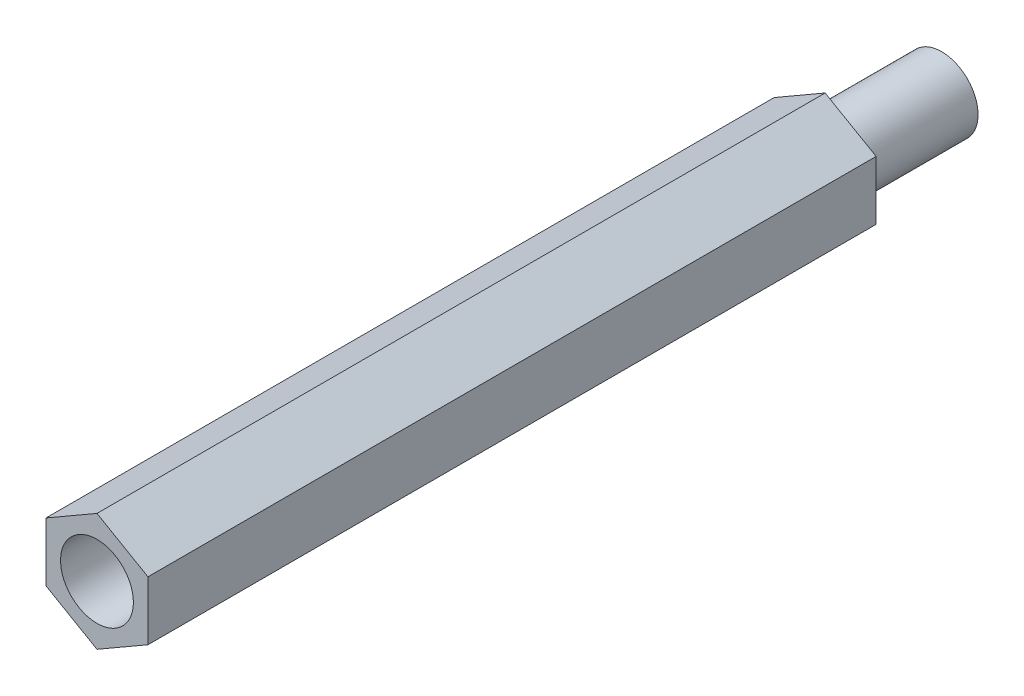
SolidWorks part; units mm, degrees
ref_plane "前视基准面" through (0, 0, 0) normal (0, 0, 1) x (1, 0, 0)
ref_plane "上视基准面" through (0, 0, 0) normal (0, 1, 0) x (1, 0, 0)
ref_plane "右视基准面" through (0, 0, 0) normal (1, 0, 0) x (0, 0, -1)
sketch "草图1" plane through (0, 0, 0) normal (0, 0, 1) x (1, 0, 0)
  line L1 (3.5, -2.0207) -> (3.5, 2.0207)
  line L2 (3.5, 2.0207) -> (0, 4.0415)
  line L3 (0, 4.0415) -> (-3.5, 2.0207)
  line L4 (-3.5, 2.0207) -> (-3.5, -2.0207)
  line L5 (-3.5, -2.0207) -> (0, -4.0415)
  line L6 (0, -4.0415) -> (3.5, -2.0207)
  circle A0 centre (0, 0) radius 3.5 construction
  dimension "D1" = 7
extrude "凸台-拉伸1" add sketch "草图1" along normal blind 60
sketch "草图2" plane through (0, 0, 0) normal (0, 0, -1) x (-1, 0, 0)
  circle A0 centre (0, 0) radius 2.5
extrude "凸台-拉伸2" add sketch "草图2" along normal blind 8
sketch "草图3" plane through (0, 0, 60) normal (0, 0, 1) x (1, 0, 0)
  circle A0 centre (0, 0) radius 2.5
extrude "切除-拉伸1" cut sketch "草图3" against normal blind 50
sketch "草图4" plane through (0, 0, 60) normal (0, 0, 1) x (1, 0, 0)
  circle A0 centre (-0.377, 0.2871) radius 11.4371
extrude "切除-拉伸2" cut sketch "草图4" against normal blind 20
sketch "草图5" plane through (0, 0, 40) normal (0, 0, 1) x (1, 0, 0)
  line L1 (0, 4.0415) -> (-3.5, 2.0207)
  line L2 (-3.5, 2.0207) -> (-3.5, -2.0207)
  line L3 (-3.5, -2.0207) -> (0, -4.0415)
  line L4 (0, -4.0415) -> (3.5, -2.0207)
  line L5 (3.5, -2.0207) -> (3.5, 2.0207)
  line L6 (3.5, 2.0207) -> (0, 4.0415)
  circle A0 centre (0, 0) radius 3.5 construction
extrude "凸台-拉伸3" add sketch "草图5" along normal blind 5
sketch "草图6" plane through (0, 0, 45) normal (0, 0, 1) x (1, 0, 0)
  circle A0 centre (0, 0) radius 2.5
extrude "切除-拉伸3" cut sketch "草图6" against normal blind 16
sketch "草图7" plane through (0, 0, 45) normal (0, 0, 1) x (1, 0, 0)
  line L0 (-3.5, 2.0207) -> (0, 4.0415)
  line L1 (0, 4.0415) -> (3.5, 2.0207)
  line L2 (3.5, 2.0207) -> (3.5, -2.0207)
  line L3 (3.5, -2.0207) -> (0, -4.0415)
  line L4 (0, -4.0415) -> (-3.5, -2.0207)
  line L5 (-3.5, -2.0207) -> (-3.5, 2.0207)
extrude "凸台-拉伸5" add sketch "草图7" along normal blind 5
sketch "草图9" plane through (0, 0, 50) normal (0, 0, 1) x (1, 0, 0)
  circle A0 centre (0, 0) radius 2.5
extrude "切除-拉伸4" cut sketch "草图9" against normal blind 5
